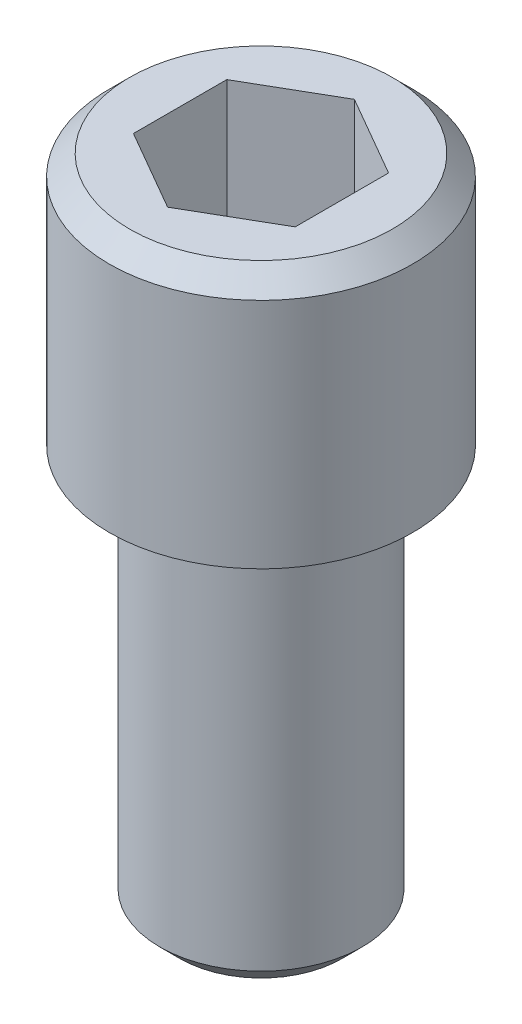
SolidWorks part; units mm, degrees
ref_plane "Přední rovina" through (0, 0, 0) normal (0, 0, 1) x (1, 0, 0)
ref_plane "Horní rovina" through (0, 0, 0) normal (0, 1, 0) x (1, 0, 0)
ref_plane "Pravá rovina" through (0, 0, 0) normal (1, 0, 0) x (0, 0, -1)
sketch "Skica1" plane through (0, 0, 0) normal (0, 1, 0) x (1, 0, 0)
  circle A0 centre (0, 0) radius 1.25
  dimension "D1" = 2.5
extrude "Přidat vysunutím1" add sketch "Skica1" along normal blind 5
sketch "Skica2" plane through (0, 5, 0) normal (0, 1, 0) x (1, 0, 0)
  circle A0 centre (0, 0) radius 1.875
  dimension "D1" = 3.75
extrude "Přidat vysunutím2" add sketch "Skica2" along normal blind 3.125
sketch "Skica3" plane through (0, 8.125, 0) normal (0, 1, 0) x (1, 0, 0)
  line L1 (0, 1.1547) -> (-1, 0.5774)
  line L2 (-1, 0.5774) -> (-1, -0.5774)
  line L3 (-1, -0.5774) -> (0, -1.1547)
  line L4 (0, -1.1547) -> (1, -0.5774)
  line L5 (1, -0.5774) -> (1, 0.5774)
  line L6 (1, 0.5774) -> (0, 1.1547)
  circle A0 centre (0, 0) radius 1 construction
  dimension "D1" = 2
extrude "Odebrat vysunutím1" cut sketch "Skica3" against normal blind 1.875
chamfer "Zkosení1" distance 0.25 angle 45 2 edges at (0, 0, 1.25) (0, 8.125, 1.875)
